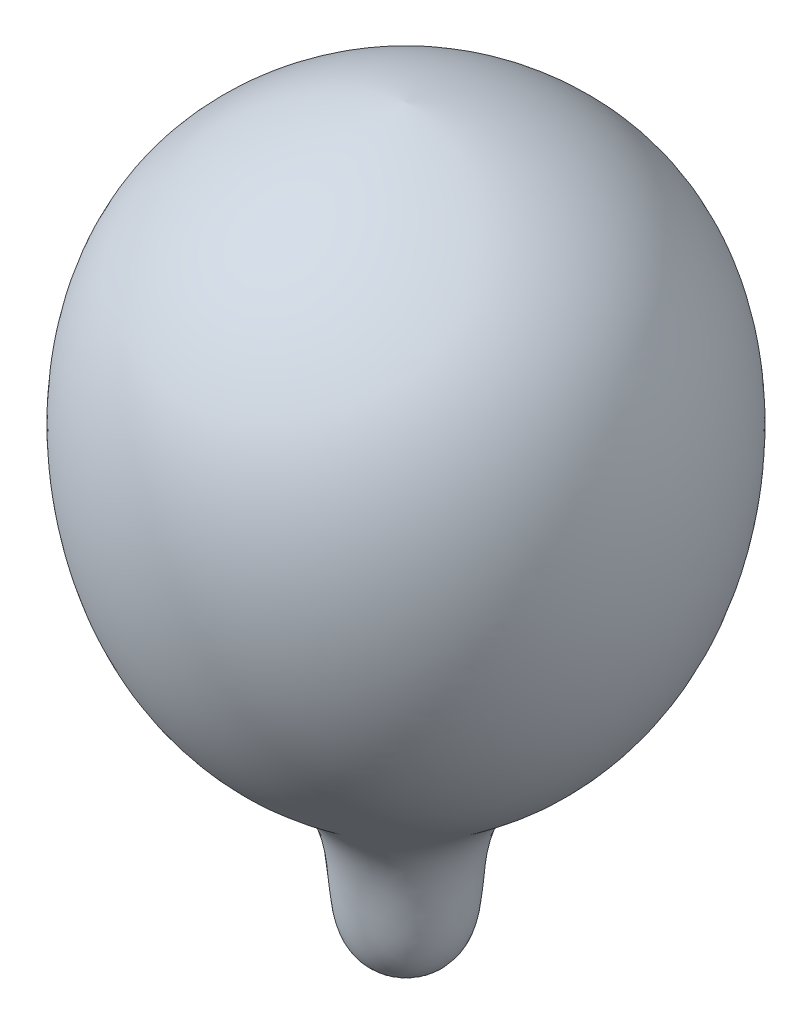
SolidWorks part; units mm, degrees
ref_plane "Front Plane"
ref_plane "Top Plane" through (0, 0, 0) normal (0, 1, 0) x (1, 0, 0)
ref_plane "Right Plane" through (0, 0, 0) normal (1, 0, 0) x (0, 0, -1)
sketch "Sketch1" plane through (0, 0, 0) normal (0, 0, 1) x (1, 0, 0)
  line L0 (170.1215, 307.7155) -> (170.1215, -418.5802)
  line L1 (0, 154.3767) -> (0, -347.2947) construction
  line L2 (-170.1215, 307.7155) -> (-170.1215, -418.5802)
  line L3 (0, -347.2947) -> (0, -406.0532)
  spline S0 degree 3 poles (0, 154.3767) (50.7896, 148.7459) (163.9011, 96.3448) (181.829, -79.7738) (121.3347, -195.7702) (45.7716, -239.5698) (33.8172, -300.6883) (37.7025, -340.3462) (0, -347.2947) knots 0 0 0 0 0.244026 0.505633 0.717447 0.831784 0.876368 1 1 1 1
  spline S1 degree 3 poles (0, 154.3767) (-50.7896, 148.7459) (-163.9011, 96.3448) (-181.829, -79.7738) (-121.3347, -195.7702) (-45.7716, -239.5698) (-33.8172, -300.6883) (-37.7025, -340.3462) (0, -347.2947) knots 0 0 0 0 0.244026 0.505633 0.717447 0.831784 0.876368 1 1 1 1
  point P21 (0.761, -348.1066)
  point P23 (0, -372.6947)
  point P24 (-0.0104, -347.3128)
  point P25 (-5.7429, -351.5406)
  point P26 (0.0082, -355.7682)
  point P27 (170.2831, -418.8373)
  point P28 (0, -406.0532)
  point P29 (170.1215, -418.5802)
  point P30 (0, -347.2947)
  dimension "D1" = 340.243
  dimension "D2" = 25.4
revolve "Revolve1" add sketch "Sketch1" angle 360 about L1
